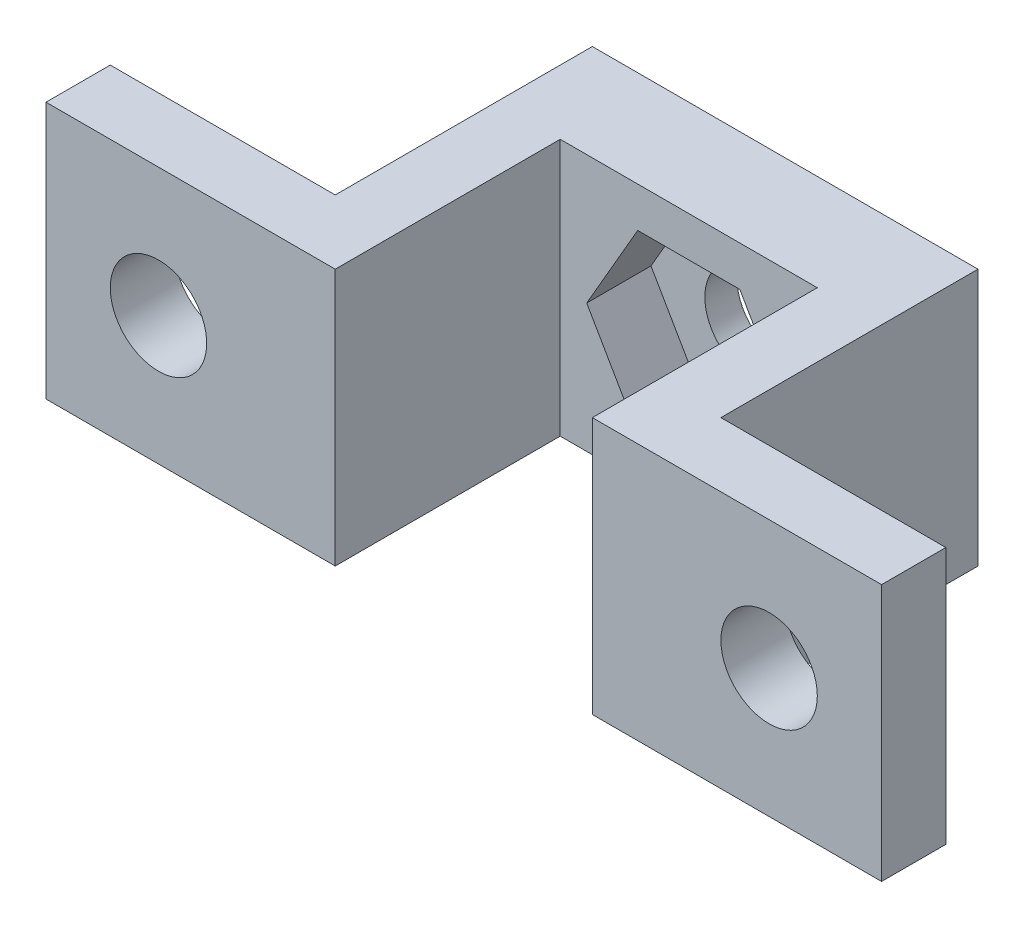
SolidWorks part; units mm, degrees
ref_plane "Ön Düzlem" through (0, 0, 0) normal (0, 0, 1) x (1, 0, 0)
ref_plane "Üst Düzlem" through (0, 0, 0) normal (0, 1, 0) x (1, 0, 0)
ref_plane "Sağ Düzlem" through (0, 0, 0) normal (1, 0, 0) x (0, 0, -1)
sketch "Çizim1" plane through (0, 0, 0) normal (0, 0, 1) x (1, 0, 0)
  line L1 (0, 0) -> (8, 0)
  line L2 (0, 0) -> (0, 8)
  line L3 (0, 8) -> (8, 8)
  line L4 (8, 0) -> (8, 8)
  dimension "D1" = 8
  dimension "D2" = 8
extrude "Yükseklik-Ekstrüzyon1" add sketch "Çizim1" along normal blind 3
sketch "Çizim2" plane through (0, 0, 3) normal (0, 0, 1) x (1, 0, 0)
  line L0 (0, 8) -> (8, 0) construction
  line L1 (8, 8) -> (0, 8) construction
  line L2 (5.5877, 6.75) -> (2.4123, 6.75)
  line L3 (2.4123, 6.75) -> (0.8246, 4)
  line L4 (0.8246, 4) -> (2.4123, 1.25)
  line L5 (2.4123, 1.25) -> (5.5877, 1.25)
  line L6 (5.5877, 1.25) -> (7.1754, 4)
  line L7 (7.1754, 4) -> (5.5877, 6.75)
  circle A0 centre (4, 4) radius 2.75 construction
  dimension "D1" = 5.5
extrude "Kes-Ekstrüzyon1" cut sketch "Çizim2" against normal blind 2
sketch "Çizim3" plane through (0, 0, 3) normal (0, 0, 1) x (1, 0, 0)
  line L0 (0, 8) -> (0, 0) construction
  line L1 (0, 8) -> (-2, 8)
  line L2 (0, 8) -> (0, 0)
  line L3 (0, 0) -> (-2, 0)
  line L4 (-2, 8) -> (-2, 0)
  line L5 (0, 0) -> (8, 0) construction
  line L6 (8, 8) -> (0, 8) construction
  line L8 (8, 8) -> (10, 8)
  line L9 (8, 8) -> (8, 0)
  line L10 (8, 0) -> (10, 0)
  line L11 (10, 8) -> (10, 0)
  dimension "D1" = 2
  dimension "D2" = 2
extrude "Yükseklik-Ekstrüzyon2" add sketch "Çizim3" along normal blind 7 and the other way blind 3
sketch "Çizim4" plane through (0, 8, 0) normal (0, 1, 0) x (1, 0, 0)
  line L1 (-2, -10) -> (-9, -10)
  line L2 (-2, -10) -> (-2, -8)
  line L3 (-2, -8) -> (-9, -8)
  line L4 (-9, -10) -> (-9, -8)
  line L5 (10, -10) -> (17, -10)
  line L6 (10, -10) -> (10, -8)
  line L7 (10, -8) -> (17, -8)
  line L8 (17, -10) -> (17, -8)
  dimension "D1" = 7
  dimension "D2" = 7
  dimension "D3" = 2
  dimension "D4" = 2
extrude "Yükseklik-Ekstrüzyon3" add sketch "Çizim4" against normal up to vertex (8 mm away)
sketch "Çizim5" plane through (0, 0, 1) normal (0, 0, 1) x (1, 0, 0)
  line L0 (0, 8) -> (8, 0) construction
  circle A0 centre (4, 4) radius 1.5
  dimension "D1" = 3
extrude "Kes-Ekstrüzyon2" cut sketch "Çizim5" against normal blind 7
sketch "Çizim7" plane through (0, 0, 8) normal (0, 0, -1) x (-1, 0, 0)
  line L0 (-17, 8) -> (-10, 0) construction
  line L1 (-4, 8) -> (-4, -0.1764) construction
  line L2 (-10, 8) -> (2, 8) construction
  circle A0 centre (-13.5, 4) radius 1.5
  circle A1 centre (5.5, 4) radius 1.5
  point P10 (0, 0)
  dimension "D1" = 3
extrude "Kes-Ekstrüzyon3" cut sketch "Çizim7" against normal blind 7
